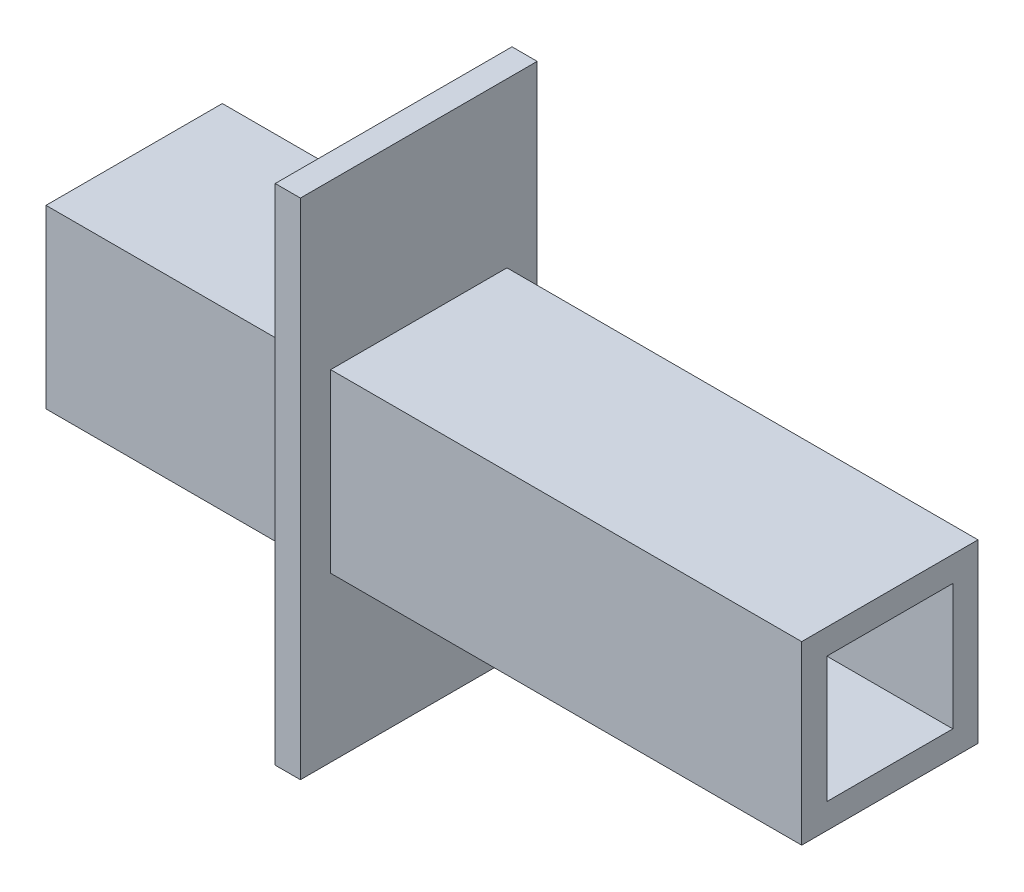
SolidWorks part; units mm, degrees
ref_plane "Alzado" through (0, 0, 0) normal (0, 0, 1) x (1, 0, 0)
ref_plane "Planta" through (0, 0, 0) normal (0, 1, 0) x (1, 0, 0)
ref_plane "Vista lateral" through (0, 0, 0) normal (1, 0, 0) x (0, 0, -1)
sketch "Croquis1" plane through (0, 0, 0) normal (1, 0, 0) x (0, 0, -1)
  line L0 (6.8792, 0) -> (-6.8792, 0) construction
  line L1 (-1.75, 0) -> (1.75, 0)
  line L2 (-1.75, 0) -> (-1.75, 3.5)
  line L3 (-1.75, 3.5) -> (1.75, 3.5)
  line L4 (1.75, 0) -> (1.75, 3.5)
  line L5 (0, 6.3461) -> (0, -6.3461) construction
  point P6 (0, 3.5)
  dimension "D1" = 3.5
  dimension "D2" = 3.5
  dimension "D3" = 0
extrude "Saliente-Extruir1" add sketch "Croquis1" along normal blind 15
ref_plane "Plano1" through (5.15, 0, 0) normal (-1, 0, 0) x (0, 0, 1)
sketch "Croquis4" plane through (5.15, 0, 0) normal (-1, 0, 0) x (0, 0, 1)
  line L0 (-1.75, 3.5) -> (1.3356, 0) construction
  line L5 (-2.35, 6.75) -> (2.35, -3.25) construction
  line L6 (-2.35, 6.75) -> (2.35, 6.75)
  line L7 (6.8792, 0) -> (-6.8792, 0) construction
  line L8 (1.75, 3.5) -> (-1.25, 0) construction
  line L9 (-2.35, 6.75) -> (-2.35, -3.25)
  line L10 (-2.35, -3.25) -> (2.35, -3.25)
  line L11 (2.35, 6.75) -> (2.35, -3.25)
  line L12 (2.35, 6.75) -> (-2.35, -3.25) construction
  line L13 (-1.75, 0) -> (-1.75, 3.5) construction
  line L15 (1.75, 3.5) -> (1.75, 0) construction
  point P2 (-0.2072, 1.75)
  point P13 (0, 1.75)
  dimension "D1" = 0.6
  dimension "D2" = 10
  dimension "D3" = 0.6
  dimension "D4" = 0
extrude "Saliente-Extruir2" add sketch "Croquis4" against normal blind 0.5
sketch "Croquis5" plane through (15, 0, 0) normal (1, 0, 0) x (0, 0, -1)
  line L1 (-1.25, 3) -> (1.25, 3)
  line L2 (-1.25, 3) -> (-1.25, 0.5)
  line L4 (1.25, 3) -> (1.25, 0.5)
  line L6 (-1.25, 0.5) -> (1.25, 0.5)
  line L7 (1.75, 3.5) -> (-1.75, 3.5) construction
  line L9 (1.75, 0) -> (1.75, 3.5) construction
  dimension "D1" = 2.5
  dimension "D2" = 2.5
  dimension "D3" = 0.5
  dimension "D4" = 0.5
extrude "Cortar-Extruir1" cut sketch "Croquis5" against normal blind 14
